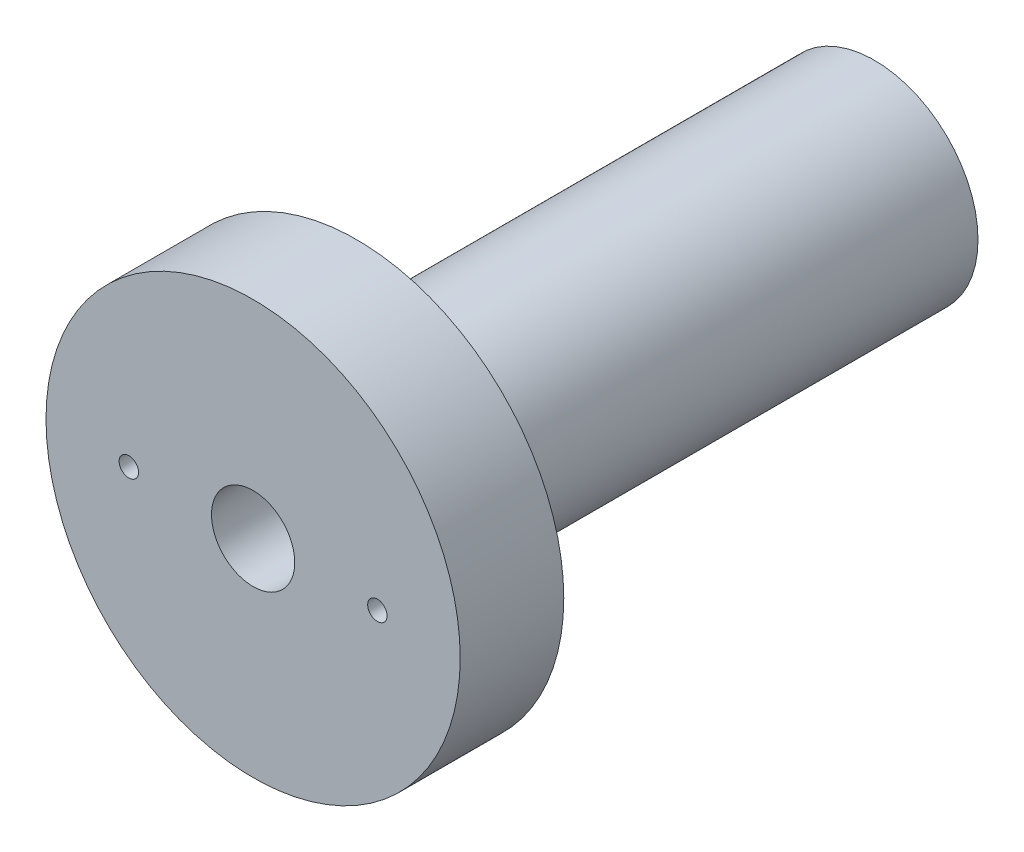
SolidWorks part; units mm, degrees
material "Delrin 2700 NC010, Low Viscosity Acetal Copolymer (SS)"
ref_plane "Front Plane" through (0, 0, 0) normal (0, 0, 1) x (1, 0, 0)
ref_plane "Top Plane" through (0, 0, 0) normal (0, 1, 0) x (1, 0, 0)
ref_plane "Right Plane" through (0, 0, 0) normal (1, 0, 0) x (0, 0, -1)
sketch "Sketch1" plane through (0, 0, 0) normal (0, 0, 1) x (1, 0, 0)
  circle A0 centre (0, 0) radius 2.5527
  circle A1 centre (0, 0) radius 6.35
  dimension "D1" = 12.7
  dimension "D2" = 5.1054
extrude "Boss-Extrude1" add sketch "Sketch1" along normal blind 31.75
sketch "Sketch2" plane through (0, 0, 31.75) normal (0, 0, 1) x (1, 0, 0)
  circle A0 centre (0, 0) radius 12.7
  circle A1 centre (0, 0) radius 2.5527
  dimension "D1" = 25.4
extrude "Boss-Extrude2" add sketch "Sketch2" along normal blind 6.35
sketch "Sketch3" plane through (0, 0, 38.1) normal (0, 0, 1) x (1, 0, 0)
  line L0 (-7.62, 0) -> (0, 0) construction
  line L1 (0, 0) -> (7.62, 0) construction
  circle A0 centre (-7.62, 0) radius 0.5953
  circle A1 centre (7.62, 0) radius 0.5953
  dimension "D2" = 1.1906
  dimension "D1" = 7.62
extrude "Cut-Extrude1" cut sketch "Sketch3" against normal through all
sketch "Sketch11" plane through (0, 0, 38.1) normal (0, 0, 1) x (1, 0, 0)
  circle A0 centre (0, 0) radius 2.5527
extrude "Boss-Extrude3" add sketch "Sketch11" against normal up to surface (38.1 mm away) up to face at (6.35, 0, 0)
hole_wizard "1/4-20 Tapped Hole3" positions "Sketch16" profile "Sketch17" tap size "1/4-20" standard "ANSI Inch" end condition through all
sketch "Sketch16" plane through (0, 0, 38.1) normal (0, 0, 1) x (1, 0, 0)
  point P0 (0, 0)
sketch "Sketch17" plane through (0, 0, 38.1) normal (1, 0, 0) x (0, -1, 0)
  line L0 (0, 0) -> (0, 38.1)
  line L1 (0, 38.1) -> (2.5527, 38.1)
  line L2 (2.5527, 38.1) -> (2.5527, 0)
  line L5 (2.5527, 0) -> (0, 0)
  line L11 (0, -6.35) -> (0, 107.95) construction
  dimension "Thru Tap Drill Dia." = 5.1054
  dimension "Thru Tap Drill Depth" = 38.1
cosmetic thread "Hole Thread2" parameters "D2"=6.35
